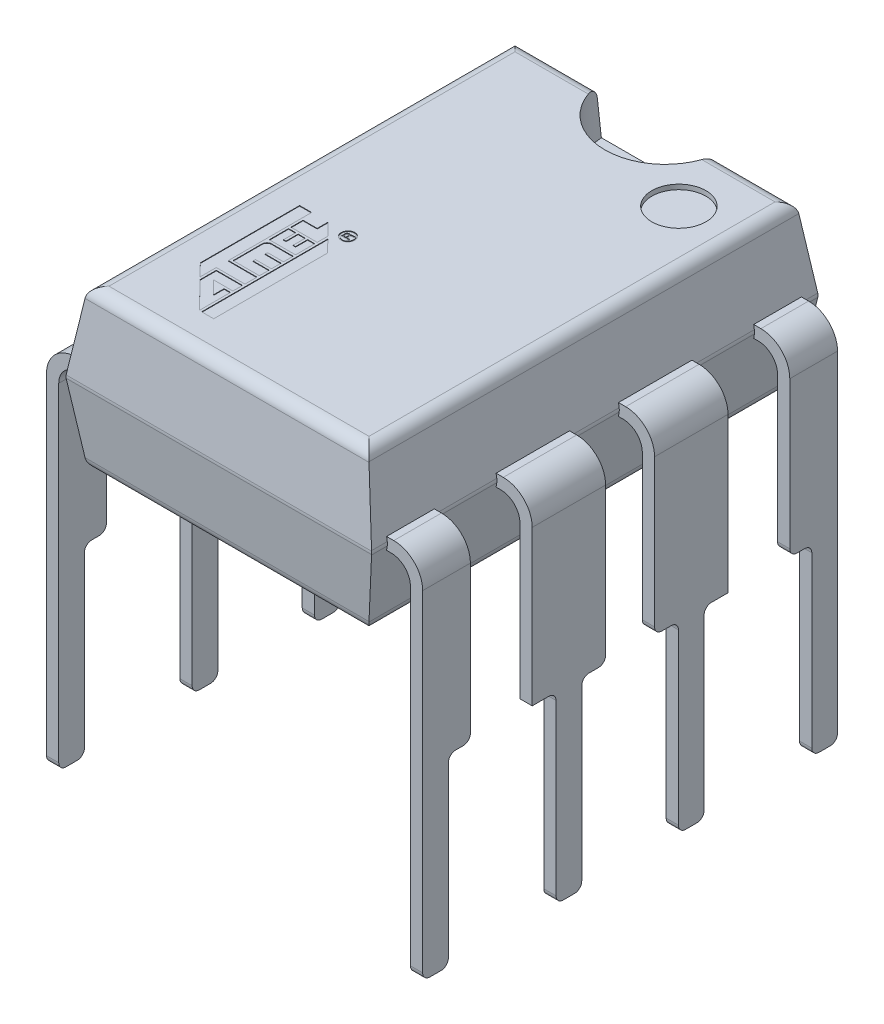
SolidWorks part; units mm, degrees
material "ABS"
ref_plane "Plano frontal" through (0, 0, 0) normal (0, 0, 1) x (1, 0, 0)
ref_plane "Plano superior" through (0, 0, 0) normal (0, 1, 0) x (1, 0, 0)
ref_plane "Plano direito" through (0, 0, 0) normal (1, 0, 0) x (0, 0, -1)
sketch "Esboço1" plane through (0, 0, 0) normal (0, 0, 1) x (1, 0, 0)
  line L0 (-3.175, 0) -> (3.175, 0) construction
  line L1 (3.1687, 0.0393) -> (2.9454, 1.4403)
  line L2 (2.6986, 1.651) -> (-2.6986, 1.651)
  line L3 (-2.9454, 1.4403) -> (-3.1687, 0.0393)
  line L4 (-3.1687, -0.0393) -> (-2.9454, -1.4403)
  line L5 (-2.6986, -1.651) -> (2.6986, -1.651)
  line L6 (3.1687, -0.0393) -> (2.9454, -1.4403)
  line L7 (-2.9119, -1.651) -> (-2.9119, 1.651) construction
  line L8 (2.9119, 1.651) -> (2.9119, -1.651) construction
  line L9 (2.9119, -1.651) -> (-2.9119, 1.651) construction
  line L10 (-2.9119, -1.651) -> (2.9119, 1.651) construction
  arc A0 (-2.6986, 1.651) -> (-2.9454, 1.4403) centre (-2.6986, 1.401) ccw
  arc A1 (-3.1687, -0.0393) -> (-3.1687, 0.0393) centre (-2.9218, 0) cw
  arc A2 (-2.9454, -1.4403) -> (-2.6986, -1.651) centre (-2.6986, -1.401) ccw
  arc A3 (2.6986, -1.651) -> (2.9454, -1.4403) centre (2.6986, -1.401) ccw
  arc A4 (3.1687, -0.0393) -> (3.1687, 0.0393) centre (2.9218, 0) ccw
  arc A5 (2.9454, 1.4403) -> (2.6986, 1.651) centre (2.6986, 1.401) ccw
  dimension "D3" = 0.25
  dimension "D1" = 6.35
  dimension "D2" = 3.302
  dimension "D4" = 5.8238
extrude "Ressalto-extrusão1" add sketch "Esboço1" along normal mid plane 9.271
sketch "Esboço2" plane through (0, 0, 0) normal (1, 0, 0) x (0, 0, -1)
  line L0 (0, 0) -> (6.8137, 0) construction
  line L1 (4.6319, 0.0301) -> (4.4621, 1.4311)
  line L2 (4.6355, -0.0393) -> (4.6355, 0.0393) construction
  line L3 (-4.6355, 1.651) -> (4.6355, 1.651) construction
  line L4 (4.214, 1.651) -> (3.6184, 1.651)
  line L5 (-4.6355, -1.651) -> (4.6355, -1.651) construction
  line L6 (4.4621, -1.4311) -> (4.6319, -0.0301)
  line L7 (3.6184, -1.651) -> (4.214, -1.651)
  line L8 (4.4355, 1.651) -> (5.0977, 1.651)
  line L9 (5.0977, 1.651) -> (5.0977, -1.651)
  line L10 (5.0977, -1.651) -> (4.4355, -1.651)
  line L11 (3.6184, 1.651) -> (3.6184, -1.651)
  line L13 (3.6184, 1.651) -> (5.0977, 1.651)
  line L14 (3.6184, 1.651) -> (3.6184, -1.651)
  line L15 (3.6184, -1.651) -> (5.0977, -1.651)
  line L16 (5.0977, 1.651) -> (5.0977, -1.651)
  arc A0 (4.4621, 1.4311) -> (4.214, 1.651) centre (4.214, 1.401) ccw
  arc A1 (4.6319, 0.0301) -> (4.6319, -0.0301) centre (4.3837, 0) cw
  arc A2 (4.214, -1.651) -> (4.4621, -1.4311) centre (4.214, -1.401) ccw
  point P20 (4.6355, 0)
  dimension "D1" = 0.25
  dimension "D2" = 0.6622
extrude "Corte-extrusão1" cut sketch "Esboço2" against normal through all both and the other way through all contours A1 L0 L9 L8 L13 A0 L1 | L0 A1 L6 A2 L15 L10 L16
mirror "Espelhar1" about plane through (0, 0, 0) normal (0, 0, 1) of "Corte-extrusão1"
ref_plane "Plano1" through (0, 0, 1.27) normal (0, 0, 1) x (1, 0, 0)
sketch "Esboço3" plane through (0, 0, 1.27) normal (0, 0, 1) x (1, 0, 0)
  line L0 (-3.904, -7.495) -> (-3.904, -0.475)
  line L1 (-3.304, 0.125) -> (3.304, 0.125)
  line L2 (3.904, -0.475) -> (3.904, -7.495)
  line L3 (3.904, -7.495) -> (3.65, -7.495)
  line L4 (3.65, -7.495) -> (3.65, -0.525)
  line L5 (3.25, -0.125) -> (-3.25, -0.125)
  line L6 (-3.65, -0.525) -> (-3.65, -7.495)
  line L7 (-3.65, -7.495) -> (-3.904, -7.495)
  line L8 (0, -0.125) -> (0, 0.125) construction
  arc A0 (3.65, -0.525) -> (3.25, -0.125) centre (3.25, -0.525) ccw
  arc A1 (-3.25, -0.125) -> (-3.65, -0.525) centre (-3.25, -0.525) ccw
  arc A2 (3.304, 0.125) -> (3.904, -0.475) centre (3.304, -0.475) cw
  arc A3 (-3.904, -0.475) -> (-3.304, 0.125) centre (-3.304, -0.475) cw
  point P17 (3.904, 0.125)
  dimension "D5" = 0.4
  dimension "D6" = 0.6
  dimension "D1" = 0.254
  dimension "D2" = 0.25
  dimension "D3" = 7.3
  dimension "D4" = 7.62
extrude "Ressalto-extrusão2" add sketch "Esboço3" along normal mid plane 1.524
ref_plane "Plano2" through (0, 0, 3.81) normal (0, 0, 1) x (1, 0, 0)
sketch "Esboço4" plane through (0, 0, 3.81) normal (0, 0, 1) x (1, 0, 0)
  line L0 (3.1687, -0.0393) -> (3.1551, -0.125) construction
  line L1 (3.1551, -0.125) -> (3.25, -0.125) construction
  line L2 (3.65, -0.525) -> (3.65, -7.495) construction
  line L3 (3.65, -7.495) -> (3.904, -7.495) construction
  line L4 (3.904, -7.495) -> (3.904, -0.475) construction
  line L5 (3.304, 0.125) -> (3.1551, 0.125) construction
  line L6 (3.1551, 0.125) -> (3.1687, 0.0393) construction
  line L7 (-3.1687, 0.0393) -> (-3.1551, 0.125) construction
  line L8 (-3.1551, 0.125) -> (-3.304, 0.125) construction
  line L9 (-3.904, -0.475) -> (-3.904, -7.495) construction
  line L10 (-3.904, -7.495) -> (-3.65, -7.495) construction
  line L11 (-3.65, -7.495) -> (-3.65, -0.525) construction
  line L12 (-3.25, -0.125) -> (-3.1551, -0.125) construction
  line L13 (-3.1551, -0.125) -> (-3.1687, -0.0393) construction
  line L14 (3.1687, -0.0393) -> (3.1551, -0.125)
  line L15 (3.1551, -0.125) -> (3.25, -0.125)
  line L16 (3.65, -0.525) -> (3.65, -7.495)
  line L17 (3.65, -7.495) -> (3.904, -7.495)
  line L18 (3.904, -7.495) -> (3.904, -0.475)
  line L19 (3.304, 0.125) -> (3.1551, 0.125)
  line L20 (3.1551, 0.125) -> (3.1687, 0.0393)
  line L21 (-3.1687, 0.0393) -> (-3.1551, 0.125)
  line L22 (-3.1551, 0.125) -> (-3.304, 0.125)
  line L23 (-3.904, -0.475) -> (-3.904, -7.495)
  line L24 (-3.904, -7.495) -> (-3.65, -7.495)
  line L25 (-3.65, -7.495) -> (-3.65, -0.525)
  line L26 (-3.25, -0.125) -> (-3.1551, -0.125)
  line L27 (-3.1551, -0.125) -> (-3.1687, -0.0393)
  arc A0 (3.1687, -0.0393) -> (3.1687, 0.0393) centre (2.9218, 0) ccw construction
  arc A1 (3.65, -0.525) -> (3.25, -0.125) centre (3.25, -0.525) ccw construction
  arc A2 (3.904, -0.475) -> (3.304, 0.125) centre (3.304, -0.475) ccw construction
  arc A3 (-3.1687, 0.0393) -> (-3.1687, -0.0393) centre (-2.9218, 0) ccw construction
  arc A4 (-3.304, 0.125) -> (-3.904, -0.475) centre (-3.304, -0.475) ccw construction
  arc A5 (-3.25, -0.125) -> (-3.65, -0.525) centre (-3.25, -0.525) ccw construction
  arc A6 (3.1687, -0.0393) -> (3.1687, 0.0393) centre (2.9218, 0) ccw
  arc A7 (3.65, -0.525) -> (3.25, -0.125) centre (3.25, -0.525) ccw
  arc A8 (3.904, -0.475) -> (3.304, 0.125) centre (3.304, -0.475) ccw
  arc A9 (-3.1687, 0.0393) -> (-3.1687, -0.0393) centre (-2.9218, 0) ccw
  arc A10 (-3.304, 0.125) -> (-3.904, -0.475) centre (-3.304, -0.475) ccw
  arc A11 (-3.25, -0.125) -> (-3.65, -0.525) centre (-3.25, -0.525) ccw
extrude "Ressalto-extrusão3" add sketch "Esboço4" along normal mid plane 0.9906
mirror "Espelhar2" about plane through (0, 0, 0) normal (0, 0, 1) of "Ressalto-extrusão2", "Ressalto-extrusão3"
sketch "Esboço5" plane through (0, 0, 0) normal (1, 0, 0) x (0, 0, -1)
  line L0 (1.882, -3.683) -> (1.6867, -3.683)
  line L1 (2.032, -7.495) -> (2.032, -0.475) construction
  line L2 (1.5367, -3.833) -> (1.5367, -7.345)
  line L3 (2.032, -7.495) -> (0.508, -7.495) construction
  line L4 (1.3867, -7.495) -> (1.1533, -7.495)
  line L5 (1.0033, -7.345) -> (1.0033, -3.833)
  line L6 (0.8533, -3.683) -> (0.658, -3.683)
  line L7 (0.508, -7.495) -> (0.508, -0.475) construction
  line L8 (0.508, -3.683) -> (0.508, -7.7594)
  line L9 (0.508, -7.7594) -> (2.032, -7.7594)
  line L10 (2.032, -7.7594) -> (2.032, -3.683)
  line L11 (2.032, -3.683) -> (1.5367, -3.683)
  line L12 (-4.214, 1.651) -> (4.214, 1.651) construction
  line L13 (3.4647, -3.683) -> (3.6219, -3.683)
  line L14 (3.3147, -7.495) -> (3.3147, -0.475) construction
  line L15 (3.7719, -3.833) -> (3.7719, -7.345)
  line L16 (4.3053, -7.495) -> (3.3147, -7.495) construction
  line L17 (3.9219, -7.495) -> (4.1553, -7.495)
  line L18 (4.3053, -7.495) -> (4.3053, -7.9729)
  line L19 (4.3053, -7.9729) -> (3.3147, -7.9729)
  line L20 (3.3147, -7.9729) -> (3.3147, -3.683)
  line L21 (0.508, -3.533) -> (0.508, -2.7844)
  line L22 (0.508, -2.7844) -> (-0.1796, -2.7844)
  line L23 (-0.1796, -2.7844) -> (-0.1796, -7.8443)
  line L24 (-0.1796, -7.8443) -> (-0.0892, -7.8443)
  line L25 (-0.1796, -7.8443) -> (0.508, -7.7594)
  line L26 (2.032, -2.7844) -> (2.622, -2.7844)
  line L27 (2.622, -2.7844) -> (2.622, -7.495)
  line L28 (2.622, -7.495) -> (2.032, -7.495)
  line L29 (3.3147, -3.533) -> (3.3147, -2.7844)
  line L30 (3.3147, -2.7844) -> (3.0353, -2.7844)
  line L31 (3.0353, -2.7844) -> (3.0353, -7.8443)
  line L32 (3.0353, -7.8443) -> (3.3147, -7.9729)
  line L33 (2.032, -3.533) -> (2.032, -2.7844)
  line L34 (2.032, -2.7844) -> (2.0505, -2.7728)
  line L35 (3.3147, -3.683) -> (3.3147, -2.7844)
  line L36 (4.3053, -7.345) -> (4.3053, -7.2012)
  line L37 (4.3053, -7.495) -> (4.3053, -0.475) construction
  line L38 (4.3053, -7.2012) -> (4.8161, -7.2012)
  line L39 (4.8161, -7.2012) -> (4.3053, -7.9729)
  arc A0 (1.1533, -7.495) -> (1.0033, -7.345) centre (1.1533, -7.345) cw
  arc A1 (1.5367, -7.345) -> (1.3867, -7.495) centre (1.3867, -7.345) cw
  arc A2 (3.7719, -7.345) -> (3.9219, -7.495) centre (3.9219, -7.345) ccw
  arc A3 (3.6219, -3.683) -> (3.7719, -3.833) centre (3.6219, -3.833) cw
  arc A4 (3.4647, -3.683) -> (3.3147, -3.533) centre (3.4647, -3.533) cw
  arc A5 (2.032, -3.533) -> (1.882, -3.683) centre (1.882, -3.533) cw
  arc A6 (1.6867, -3.683) -> (1.5367, -3.833) centre (1.6867, -3.833) ccw
  arc A7 (0.8533, -3.683) -> (1.0033, -3.833) centre (0.8533, -3.833) cw
  arc A8 (0.508, -3.533) -> (0.658, -3.683) centre (0.658, -3.533) ccw
  arc A9 (4.1553, -7.495) -> (4.3053, -7.345) centre (4.1553, -7.345) ccw
  point P42 (1.0033, -7.495)
  point P45 (1.5367, -7.495)
  point P48 (3.7719, -7.495)
  point P56 (2.032, -3.683)
  dimension "D3" = 0.15
  dimension "D4" = 0.15
  dimension "D5" = 0.15
  dimension "D6" = 0.15
  dimension "D7" = 0.15
  dimension "D8" = 0.15
  dimension "D9" = 0.15
  dimension "D10" = 0.15
  dimension "D11" = 0.15
  dimension "D12" = 0.15
  dimension "D1" = 5.334
  dimension "D2" = 0.5334
extrude "Corte-extrusão3" cut sketch "Esboço5" against normal through all both and the other way through all contours L9 L10 L0 L2 L4 L5 L6 L8 | L20 L19 L18 L17 L15 L13
mirror "Espelhar3" about plane through (0, 0, 0) normal (0, 0, 1) of "Corte-extrusão3"
sketch "Esboço7" plane through (0, 1.651, 0) normal (0, 1, 0) x (1, 0, 0)
  line L0 (-3.17, 4.6319) -> (3.17, 4.6319) construction
  line L1 (1.25, 4.6319) -> (-1.25, 4.6319)
  arc A0 (-1.25, 4.6319) -> (1.25, 4.6319) centre (0, 4.6319) ccw
  dimension "D1" = 2.5
extrude "Corte-extrusão4" cut sketch "Esboço7" against normal blind 0.9906
sketch "Esboço8" plane through (0, 1.651, 0) normal (0, 1, 0) x (1, 0, 0)
  line L0 (-1.0257, -3.7127) -> (-1.3257, -3.7127)
  line L1 (-1.3257, -3.7127) -> (-2.17, -2.8467)
  line L2 (-2.17, -2.8467) -> (-2.17, -0.484)
  line L3 (-2.17, -0.484) -> (-1.3257, -0.484)
  line L4 (-1.3257, -0.484) -> (-1.0257, -0.7917)
  line L5 (-1.0257, -0.7917) -> (-1.0257, -3.7127)
  line L6 (-1.5757, -0.7858) -> (-2.17, -0.7858)
  line L7 (-1.3257, -3.7127) -> (-1.3257, -0.484) construction
  line L8 (-1.92, -0.484) -> (-1.92, -2.5145)
  line L9 (-1.92, -2.5145) -> (-1.3257, -2.5145)
  line L10 (-1.92, -2.7645) -> (-1.92, -3.1031)
  line L11 (-1.92, -2.7645) -> (-1.3257, -2.7645)
  line L12 (-1.3257, -2.4645) -> (-1.87, -2.4645)
  line L13 (-1.87, -2.4645) -> (-1.87, -1.8645)
  line L14 (-1.77, -1.7645) -> (-1.3257, -1.7645)
  line L15 (-1.3257, -1.7645) -> (-1.3257, -1.9645)
  line L16 (-1.3257, -1.9645) -> (-1.636, -1.9645)
  line L17 (-1.656, -1.9845) -> (-1.656, -2.0145)
  line L18 (-1.656, -2.0145) -> (-1.3257, -2.0145)
  line L19 (-1.3257, -2.0145) -> (-1.3257, -2.2145)
  line L20 (-1.3257, -2.2145) -> (-1.656, -2.2145)
  line L21 (-1.656, -2.2145) -> (-1.656, -2.2645)
  line L22 (-1.656, -2.2645) -> (-1.3257, -2.2645)
  line L23 (-1.87, -1.3145) -> (-1.87, -1.7145)
  line L24 (-1.87, -1.7145) -> (-1.3257, -1.7145)
  line L25 (-1.3257, -1.7145) -> (-1.3257, -1.3145)
  line L26 (-1.5238, -1.3145) -> (-1.6719, -1.3145)
  line L27 (-1.5238, -1.3145) -> (-1.5238, -1.5645)
  line L28 (-1.5238, -1.5645) -> (-1.4738, -1.5645)
  line L29 (-1.4738, -1.5645) -> (-1.4738, -1.3145)
  line L30 (-1.2757, -3.7127) -> (-1.2757, -1.0936)
  line L31 (-1.6719, -1.3145) -> (-1.6719, -1.5645)
  line L32 (-1.6719, -1.5645) -> (-1.7219, -1.5645)
  line L33 (-1.7219, -1.5645) -> (-1.7219, -1.3145)
  line L34 (-1.7219, -1.3145) -> (-1.87, -1.3145)
  line L35 (-1.0257, -1.35) -> (-1.87, -0.484)
  line L36 (-1.87, -1.2645) -> (-1.87, -1.0145)
  line L37 (-1.87, -1.0145) -> (-1.5757, -1.0145)
  line L38 (-1.5757, -1.0145) -> (-1.5757, -0.7858)
  line L39 (-1.87, -1.2645) -> (-1.3257, -1.2645)
  line L40 (-1.3257, -3.709) -> (-1.87, -3.1507)
  line L41 (-1.87, -3.1507) -> (-1.87, -2.8145)
  line L42 (-1.87, -2.8145) -> (-1.3257, -2.8145)
  line L43 (-1.3257, -2.8145) -> (-1.3257, -3.0145)
  line L44 (-1.3257, -3.0145) -> (-1.7234, -3.0145)
  line L45 (-1.7234, -3.0145) -> (-1.4583, -3.2865)
  line L46 (-1.4583, -3.2865) -> (-1.4583, -3.0645)
  line L47 (-1.4583, -3.0645) -> (-1.3257, -3.0645)
  line L48 (-1.3257, -1.3145) -> (-1.4738, -1.3145)
  line L49 (-1.3257, -3.709) -> (-1.3257, -3.0645)
  line L50 (-1.3257, -3.0145) -> (-1.3257, -2.8145)
  line L51 (-1.3257, -2.7645) -> (-1.3257, -2.5145)
  line L52 (-1.3257, -2.4645) -> (-1.3257, -2.2645)
  line L53 (-1.3257, -1.9645) -> (-1.3257, -2.4202)
  line L54 (-1.3257, -1.2645) -> (-1.3257, -1.0423)
  arc A0 (-1.87, -1.8645) -> (-1.77, -1.7645) centre (-1.77, -1.8645) cw
  arc A1 (-1.636, -1.9645) -> (-1.656, -1.9845) centre (-1.636, -1.9845) ccw
  point P60 (-1.87, -1.7645)
  point P63 (-1.656, -1.9645)
  dimension "D20" = 0.1
  dimension "D21" = 0.02
  dimension "D1" = 0.25
  dimension "D2" = 0.25
  dimension "D3" = 0.25
  dimension "D4" = 0.25
  dimension "D5" = 0.2
  dimension "D6" = 0.05
  dimension "D7" = 0.05
  dimension "D8" = 0.25
  dimension "D9" = 3.2288
  dimension "D10" = 0.05
  dimension "D11" = 0.05
  dimension "D12" = 0.05
  dimension "D13" = 0.05
  dimension "D14" = 0.2
  dimension "D15" = 0.05
  dimension "D16" = 0.05
  dimension "D17" = 0.05
  dimension "D18" = 0.2
  dimension "D19" = 0.25
  dimension "D22" = 0.05
  dimension "D23" = 0.4
extrude "Corte-extrusão5" cut sketch "Esboço8" against normal blind 0.01 contours L5 L35 L30 L0 | L40 L49 L47 L46 L45 L44 L43 L42 L41 | L11 L51 L9 L8 L3 L2 L1 L10 | A1 L16 L15 L14 A0 L13 L12 L52 L22 L21 L20 L19 L18 L17 | L25 L48 L29 L28 L27 L26 L31 L32 L33 L34 L23 L24 | L39 L54 L35 L38 L37 L36
sketch "Esboço9" plane through (0, 1.651, 0) normal (0, 1, 0) x (1, 0, 0)
  text T0 "<r90> ®</r>" font "Century Gothic" height in points 1
extrude "Corte-extrusão6" cut sketch "Esboço9" against normal blind 0.01
sketch "Esboço10" plane through (0, 1.651, 0) normal (0, 1, 0) x (1, 0, 0)
  circle A0 centre (1.7786, 3.1382) radius 0.5614
extrude "Corte-extrusão7" cut sketch "Esboço10" against normal blind 0.1
